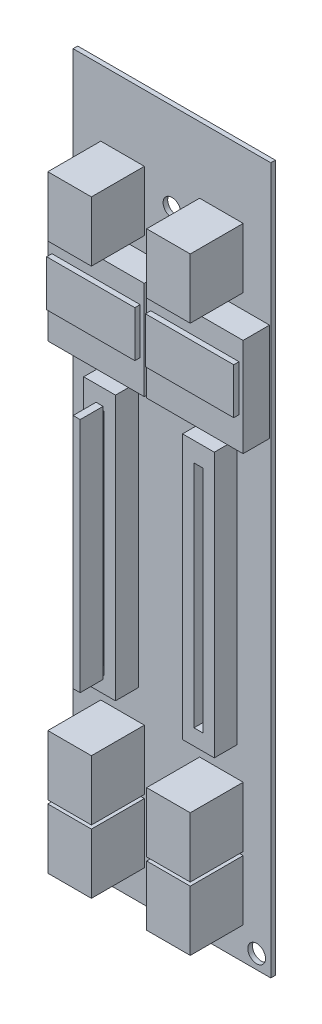
SolidWorks part; units mm, degrees
ref_plane "Front Plane" through (0, 0, 0) normal (0, 0, 1) x (1, 0, 0)
ref_plane "Top Plane" through (0, 0, 0) normal (0, 1, 0) x (1, 0, 0)
ref_plane "Right Plane" through (0, 0, 0) normal (1, 0, 0) x (0, 0, -1)
sketch "Sketch1" plane through (0, 0, 0) normal (0, 0, 1) x (1, 0, 0)
  line L0 (0, 0) -> (3.7316, 0)
  line L1 (0, 0) -> (56, 0)
  line L2 (0, 0) -> (0, 200)
  line L3 (0, 200) -> (56, 200)
  line L4 (56, 0) -> (56, 200)
  line L5 (0, 0) -> (10.2, 0)
  line L6 (10.2, 0) -> (10.2, 10)
  line L7 (0, 0) -> (38.2, 0)
  line L8 (38.2, 0) -> (38.2, 10)
  line L9 (10.2, 10) -> (10.2, 9.125)
  line L10 (10.2, 9.125) -> (7.835, 9.125)
  line L11 (7.835, 9.125) -> (7.835, 26.125)
  line L12 (7.835, 26.125) -> (20.185, 26.125)
  line L13 (20.185, 26.125) -> (20.185, 9.125)
  line L14 (20.185, 9.125) -> (10.2, 9.125)
  line L15 (38.2, 10) -> (38.2, 9.125)
  line L16 (38.2, 9.125) -> (35.835, 9.125)
  line L17 (35.835, 9.125) -> (35.835, 26.125)
  line L18 (35.835, 26.125) -> (48.185, 26.125)
  line L19 (48.185, 26.125) -> (48.185, 9.125)
  line L20 (48.185, 9.125) -> (38.2, 9.125)
  line L21 (7.835, 26.125) -> (7.835, 27.125)
  line L22 (7.835, 27.125) -> (20.185, 27.125)
  line L23 (20.185, 27.125) -> (20.185, 44.125)
  line L24 (20.185, 44.125) -> (7.835, 44.125)
  line L25 (7.835, 44.125) -> (7.835, 27.125)
  line L26 (35.835, 27.125) -> (48.185, 27.125)
  line L27 (48.185, 27.125) -> (48.185, 44.125)
  line L28 (48.185, 44.125) -> (35.835, 44.125)
  line L29 (35.835, 44.125) -> (35.835, 27.125)
  line L30 (10.2, 164.225) -> (7.835, 164.225)
  line L31 (20.185, 181.225) -> (20.185, 164.225)
  line L32 (7.835, 181.225) -> (20.185, 181.225)
  line L33 (7.835, 164.225) -> (7.835, 181.225)
  line L34 (10.2, 164.225) -> (20.185, 164.225)
  line L35 (38.2, 164.225) -> (35.835, 164.225)
  line L36 (48.185, 181.225) -> (48.185, 164.225)
  line L37 (35.835, 181.225) -> (48.185, 181.225)
  line L38 (35.835, 164.225) -> (35.835, 181.225)
  line L39 (38.2, 164.225) -> (48.185, 164.225)
  line L40 (28, 0) -> (28, 175)
  circle A0 centre (4, 4) radius 2.5
  circle A1 centre (52, 4) radius 2.5
  circle A2 centre (28, 175) radius 2.5
  dimension "D1" = 2
  dimension "D2" = 2
  dimension "D3" = 2
  dimension "D4" = 2
extrude "Boss-Extrude1" add sketch "Sketch1" along normal blind 1.3
sketch "Sketch2" plane through (0, 0, 1.3) normal (0, 0, 1) x (1, 0, 0)
  line L1 (20.185, 181.225) -> (7.835, 181.225)
  line L2 (20.185, 181.225) -> (20.185, 164.225)
  line L3 (20.185, 164.225) -> (7.835, 164.225)
  line L4 (7.835, 181.225) -> (7.835, 164.225)
  line L5 (48.185, 181.225) -> (35.835, 181.225)
  line L6 (48.185, 181.225) -> (48.185, 164.225)
  line L7 (48.185, 164.225) -> (35.835, 164.225)
  line L8 (35.835, 181.225) -> (35.835, 164.225)
  line L9 (48.185, 44.125) -> (35.835, 44.125)
  line L10 (48.185, 44.125) -> (48.185, 27.125)
  line L11 (48.185, 27.125) -> (35.835, 27.125)
  line L12 (35.835, 44.125) -> (35.835, 27.125)
  line L13 (48.185, 26.125) -> (35.835, 26.125)
  line L14 (48.185, 26.125) -> (48.185, 9.125)
  line L15 (48.185, 9.125) -> (35.835, 9.125)
  line L16 (35.835, 26.125) -> (35.835, 9.125)
  line L17 (20.185, 26.125) -> (7.835, 26.125)
  line L18 (20.185, 26.125) -> (20.185, 9.125)
  line L19 (20.185, 9.125) -> (7.835, 9.125)
  line L20 (7.835, 26.125) -> (7.835, 9.125)
  line L21 (20.185, 44.125) -> (7.835, 44.125)
  line L22 (20.185, 44.125) -> (20.185, 27.125)
  line L23 (20.185, 27.125) -> (7.835, 27.125)
  line L24 (7.835, 44.125) -> (7.835, 27.125)
extrude "Boss-Extrude2" add sketch "Sketch2" along normal blind 15 and the other way blind 1.3
sketch "Sketch3" plane through (0, 0, 1.3) normal (0, 0, 1) x (1, 0, 0)
  line L0 (0, 0) -> (0, 160)
  line L1 (0, 0) -> (0, 200) construction
  line L2 (0, 160) -> (56, 160)
  line L3 (56, 0) -> (56, 200) construction
  line L4 (0, 160) -> (56, 160)
  line L5 (0, 160) -> (56, 160)
  line L6 (28, 160) -> (27.65, 160)
  line L7 (27.65, 160) -> (27.65, 132.2)
  line L8 (27.65, 132.2) -> (0.35, 132.2)
  line L9 (0.35, 132.2) -> (0.35, 160)
  line L10 (28, 160) -> (28, 162.4851)
  line L11 (55.65, 132.2) -> (55.65, 160)
  line L12 (28.35, 132.2) -> (55.65, 132.2)
  line L13 (28.35, 160) -> (28.35, 132.2)
  line L14 (28, 160) -> (28.35, 160)
extrude "Boss-Extrude3" add sketch "Sketch3" along normal blind 7.5 contours L9 L8 L7 L5 | L5 L13 L12 L11
sketch "Sketch4" plane through (0, 0, 8.8) normal (0, 0, 1) x (1, 0, 0)
  line L0 (14, 160) -> (1.5, 160)
  line L1 (0.35, 160) -> (27.65, 160) construction
  line L2 (0.35, 160) -> (27.65, 160) construction
  line L3 (1.5, 160) -> (1.5, 154.2)
  line L4 (1.5, 154.2) -> (1.5, 141.2)
  line L5 (1.5, 141.2) -> (26.5, 141.2)
  line L6 (26.5, 141.2) -> (26.5, 154.2)
  line L7 (26.5, 154.2) -> (1.5, 154.2)
  line L8 (29.5, 154.2) -> (29.5, 141.2)
  line L9 (29.5, 141.2) -> (54.5, 141.2)
  line L10 (54.5, 141.2) -> (54.5, 154.2)
  line L11 (54.5, 154.2) -> (29.5, 154.2)
  line L12 (14, 141.2) -> (14, 132.2)
  line L13 (27.65, 132.2) -> (0.35, 132.2) construction
  point P10 (0, 0)
  dimension "D1" = 2
extrude "Boss-Extrude4" add sketch "Sketch4" along normal blind 1.5 contours L6 L7 L4 L5 | L10 L11 L8 L9
sketch "Sketch5" plane through (0, 0, 1.3) normal (0, 0, 1) x (1, 0, 0)
  line L0 (0, 0) -> (9.5, 0)
  line L1 (9.5, 0) -> (9.5, 52.5)
  line L2 (9.5, 52.5) -> (18.5, 52.5)
  line L3 (18.5, 52.5) -> (18.5, 127.5)
  line L4 (18.5, 127.5) -> (9.5, 127.5)
  line L5 (9.5, 127.5) -> (9.5, 52.5)
  line L6 (9.5, 52.5) -> (9.5, 57)
  line L7 (9.5, 57) -> (12.75, 57)
  line L8 (12.75, 57) -> (12.75, 122)
  line L9 (12.75, 122) -> (15.25, 122)
  line L10 (15.25, 122) -> (15.25, 57)
  line L11 (15.25, 57) -> (12.75, 57)
  line L12 (37.5, 52.5) -> (46.5, 52.5)
  line L13 (46.5, 52.5) -> (46.5, 127.5)
  line L14 (46.5, 127.5) -> (37.5, 127.5)
  line L15 (37.5, 127.5) -> (37.5, 52.5)
  line L16 (37.5, 52.5) -> (37.5, 57)
  line L17 (37.5, 57) -> (40.75, 57)
  line L18 (40.75, 57) -> (40.75, 122)
  line L19 (40.75, 122) -> (43.25, 122)
  line L20 (43.25, 122) -> (43.25, 57)
  line L21 (43.25, 57) -> (40.75, 57)
  point P5 (0, 0)
  dimension "D1" = 2
extrude "Boss-Extrude5" add sketch "Sketch5" along normal blind 6.5
sketch "Sketch7" plane through (0, 0, 7.8) normal (0, 0, 1) x (1, 0, 0)
  line L0 (14, 122) -> (14, 123)
  line L1 (12.75, 122) -> (15.25, 122) construction
  line L2 (14, 123) -> (14, 56)
  line L3 (14, 123) -> (13, 123)
  line L4 (13, 123) -> (13, 56)
  line L5 (13, 56) -> (15, 56)
  line L6 (15, 56) -> (15, 123)
  line L7 (15, 123) -> (14, 123)
  line M2 (15.25, 57) -> (12.75, 57)
  line M4 (12.75, 122) -> (15.25, 122)
extrude "Boss-Extrude6" add sketch "Sketch7" along normal blind 6.5 contours L3 L4 L0 M4 | L6 L7 L0 M4 | L4 L2 M4 M2 | L6 L2 M2 M4 | L5 L6 L2 M2 | L4 L5 L2 M2
sketch "Sketch13" plane through (0, 0, 1.3) normal (0, 0, 1) x (1, 0, 0)
